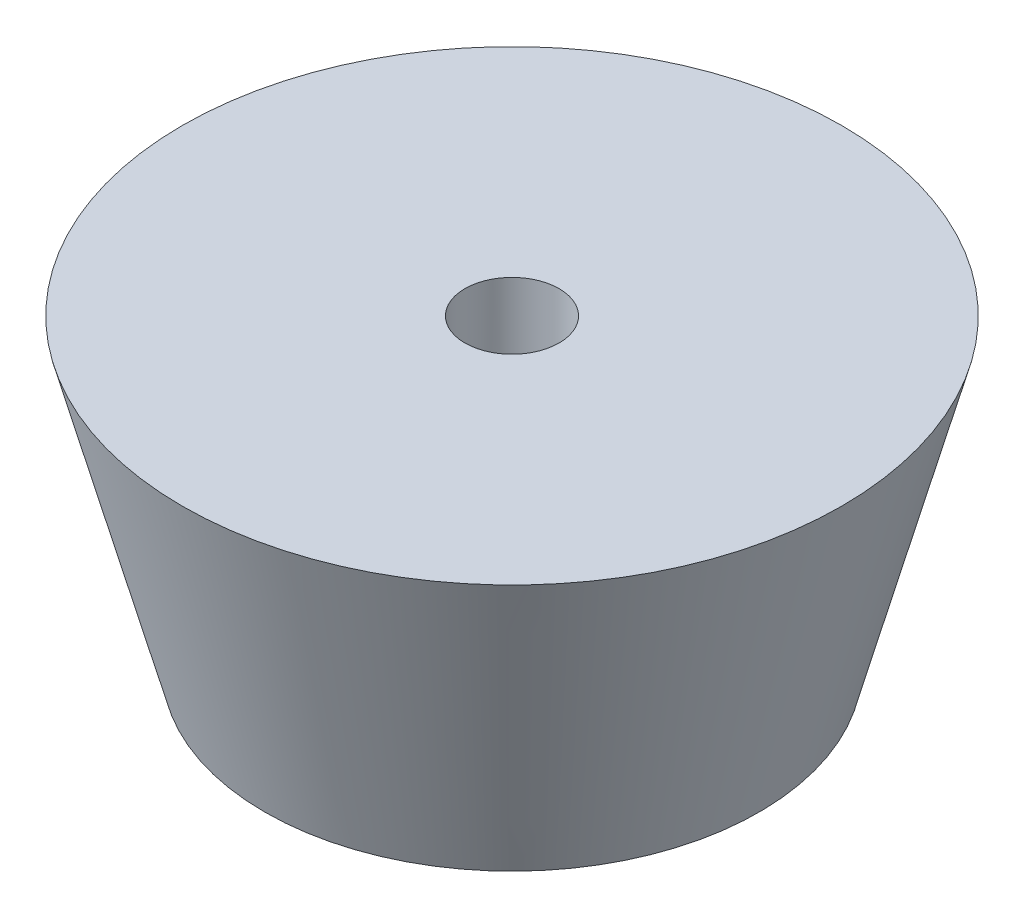
SolidWorks part; units mm, degrees
material "Полиуретан (11671)"
ref_plane "Спереди" through (0, 0, 0) normal (0, 0, 1) x (1, 0, 0)
ref_plane "Сверху" through (0, 0, 0) normal (0, 1, 0) x (1, 0, 0)
ref_plane "Справа" through (0, 0, 0) normal (1, 0, 0) x (0, 0, -1)
sketch "Эскиз1" plane through (0, 0, 0) normal (0, 1, 0) x (1, 0, 0)
  circle A0 centre (0, 0) radius 10.5
ref_plane "Плоскость1" through (0, 13, 0) normal (0, 1, 0) x (1, 0, 0)
sketch "Эскиз2" plane through (0, 13, 0) normal (0, 1, 0) x (1, 0, 0)
  circle A0 centre (0, 0) radius 14
loft "По сечениям1" add profiles "Эскиз2", "Эскиз1"
sketch "Эскиз3" plane through (0, 0, 0) normal (0, -1, 0) x (1, 0, 0)
  circle A0 centre (0, 0) radius 6.5
extrude "Вырез-Вытянуть1" cut sketch "Эскиз3" against normal blind 10
sketch "Эскиз4" plane through (0, 10, 0) normal (0, -1, 0) x (1, 0, 0)
  circle A0 centre (0, 0) radius 2
extrude "Вырез-Вытянуть2" cut sketch "Эскиз4" against normal through all
